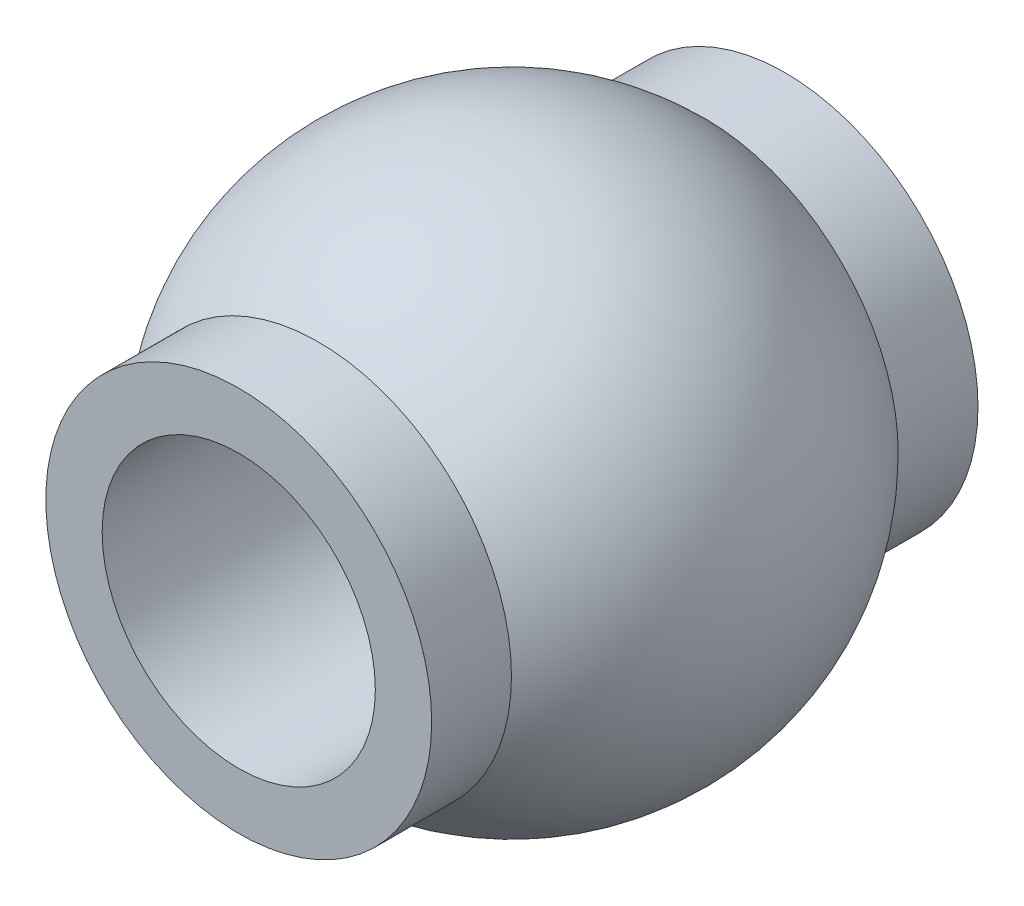
SolidWorks part; units mm, degrees
material "Alloy Steel"
ref_plane "Front Plane" through (0, 0, 0) normal (0, 0, 1) x (1, 0, 0)
ref_plane "Top Plane" through (0, 0, 0) normal (0, 1, 0) x (1, 0, 0)
ref_plane "Right Plane" through (0, 0, 0) normal (1, 0, 0) x (0, 0, -1)
sketch "Sketch1" plane through (0, 0, 0) normal (0, 0, 1) x (1, 0, 0)
  line L0 (0, -11.1125) -> (0, 11.1125) construction
  line L1 (0, 11.1125) -> (0, -11.1125)
  arc A0 (0, 11.1125) -> (0, -11.1125) centre (0, 0) cw
  dimension "D1" = 11.1125
revolve "Revolve1" add sketch "Sketch1" angle 360 about L0
sketch "Sketch2" plane through (0, 0, 0) normal (0, 0, 1) x (1, 0, 0)
  circle A0 centre (0, 0) radius 5.5562
  dimension "D1" = 11.1125
extrude "Extrude1" cut sketch "Sketch2" against normal mid plane 50.8
sketch "Sketch5" plane through (0, 0, 0) normal (1, 0, 0) x (0, 0, -1)
  line L0 (-7.8668, 7.8486) -> (-7.8668, -7.8486)
  arc A0 (9.6237, 5.5562) -> (-9.6237, 5.5563) centre (0, 0) ccw construction
  arc A1 (-9.6237, -5.5562) -> (9.6237, -5.5562) centre (0, 0) ccw construction
  arc A2 (9.6237, 5.5562) -> (-9.6237, 5.5563) centre (0, 0) ccw
  arc A3 (-9.6237, -5.5562) -> (9.6237, -5.5562) centre (0, 0) ccw
  dimension "D1" = 15.6972
ref_plane "Plane1" through (0, 0, 7.8668) normal (0, 0, 1) x (1, 0, 0)
sketch "Sketch3" plane through (0, 0, 7.8668) normal (0, 0, 1) x (1, 0, 0)
  circle A0 centre (0, 0) radius 11.1125 construction
  circle A1 centre (0, 0) radius 11.1125
extrude "Extrude2" cut sketch "Sketch3" along normal up to next
sketch "Sketch4" plane through (0, 0, 7.8668) normal (0, 0, 1) x (1, 0, 0)
  circle A0 centre (0, 0) radius 7.8486 construction
  circle A1 centre (0, 0) radius 5.5562 construction
  circle A2 centre (0, 0) radius 7.8486
  circle A3 centre (0, 0) radius 5.5562
extrude "Boss-Extrude1" add sketch "Sketch4" along normal offset from surface (3.2457 mm away) 11.1125 up to plane "Front Plane"
mirror "Mirror1" about plane through (0, 0, 0) normal (0, 0, 1) of "Extrude2"
sketch "Sketch6" plane through (0, 0, -7.8668) normal (0, 0, -1) x (-1, 0, 0)
  circle A0 centre (0, 0) radius 5.5562 construction
  circle A1 centre (0, 0) radius 7.8486 construction
  circle A2 centre (0, 0) radius 5.5562
  circle A3 centre (0, 0) radius 7.8486
extrude "Boss-Extrude2" add sketch "Sketch6" along normal offset from surface (3.2457 mm away) 11.1125 up to plane "Front Plane" offset beyond the face yes
